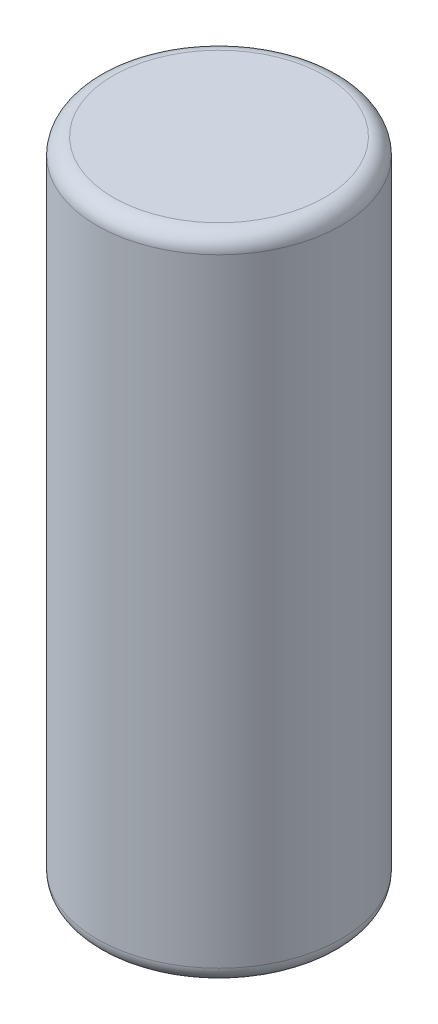
SolidWorks part; units mm, degrees
material "Plain Carbon Steel"
ref_plane "Front Plane" through (0, 0, 0) normal (0, 0, 1) x (1, 0, 0)
ref_plane "Top Plane" through (0, 0, 0) normal (0, 1, 0) x (1, 0, 0)
ref_plane "Right Plane" through (0, 0, 0) normal (1, 0, 0) x (0, 0, -1)
sketch "Sketch1" plane through (0, 0, 0) normal (0, 1, 0) x (1, 0, 0)
  circle A0 centre (0, 0) radius 75
  dimension "D1" = 150
extrude "Boss-Extrude1" add sketch "Sketch1" along normal blind 400
fillet "Fillet1" radius 10 1 edges at (0, 400, 75)
fillet "Fillet2" radius 10 1 edges at (0, 0, 75)
ref_plane "Plane1" through (0, 0, 90) normal (0, 0, 1) x (1, 0, 0)
sketch "Sketch2" plane through (0, 400, 0) normal (0, 1, 0) x (1, 0, 0)
  line L0 (0, 0) -> (0, 200.0952) construction
